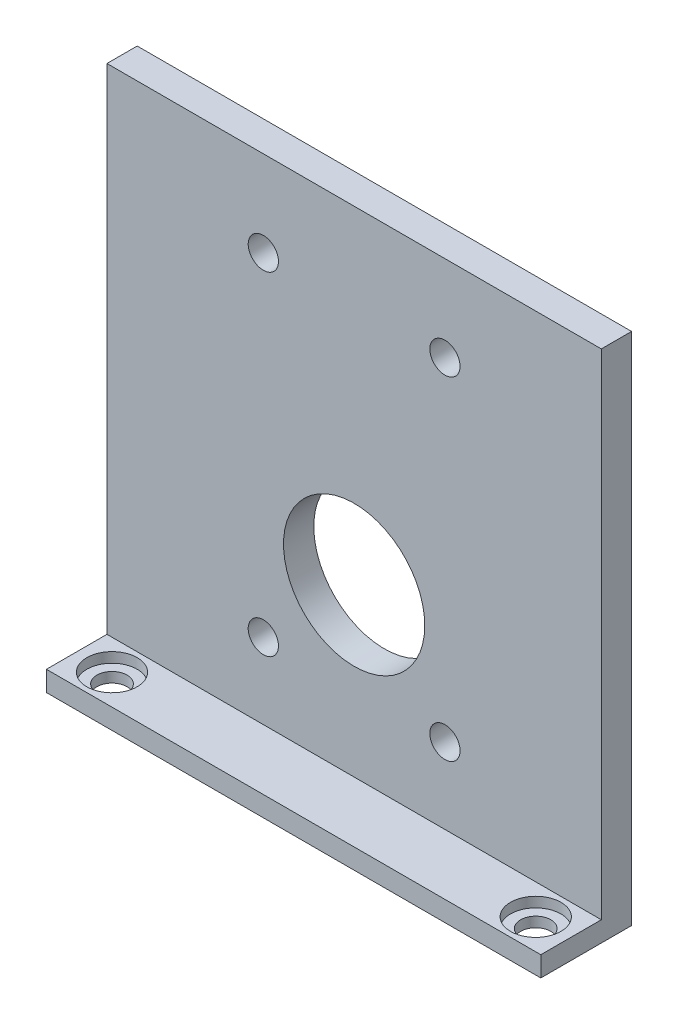
SolidWorks part; units mm, degrees
ref_plane "Front Plane" through (0, 0, 0) normal (0, 0, 1) x (1, 0, 0)
ref_plane "Top Plane" through (0, 0, 0) normal (0, 1, 0) x (1, 0, 0)
ref_plane "Right Plane" through (0, 0, 0) normal (1, 0, 0) x (0, 0, -1)
sketch "Sketch1" plane through (0, 0, 0) normal (0, 1, 0) x (1, 0, 0)
  line L1 (-24.5, 4.5) -> (24.5, 4.5)
  line L2 (-24.5, 4.5) -> (-24.5, -4.5)
  line L3 (-24.5, -4.5) -> (24.5, -4.5)
  line L4 (24.5, 4.5) -> (24.5, -4.5)
  line L5 (-24.5, 4.5) -> (24.5, -4.5) construction
  line L6 (-24.5, -4.5) -> (24.5, 4.5) construction
  point P0 (0, 0)
  dimension "D1" = 9
  dimension "D2" = 49
extrude "Boss-Extrude1" add sketch "Sketch1" along normal blind 2
sketch "Sketch2" plane through (0, 2, 0) normal (0, 1, 0) x (1, 0, 0)
  line L0 (-24.5, 1.5) -> (24.5, 1.5) construction
  line L1 (-24.5, 4.5) -> (-24.5, -4.5) construction
  line L2 (24.5, -4.5) -> (24.5, 4.5) construction
  line L3 (24.5, 4.5) -> (-24.5, 4.5) construction
  line L5 (-24.5, 4.5) -> (24.5, 4.5)
  line L6 (-24.5, 4.5) -> (-24.5, 1.5)
  line L7 (-24.5, 1.5) -> (24.5, 1.5)
  line L8 (24.5, 4.5) -> (24.5, 1.5)
  dimension "D1" = 3
extrude "Boss-Extrude2" add sketch "Sketch2" along normal blind 49
sketch "Sketch3" plane through (0, 0, -1.5) normal (0, 0, 1) x (1, 0, 0)
  line L0 (0, 2) -> (0, 51) construction
  line L1 (-24.5, 2) -> (24.5, 2) construction
  line L2 (-24.5, 51) -> (24.5, 51) construction
  line L3 (-24.5, 49.5) -> (24.5, 49.5) construction
  line L4 (-24.5, 51) -> (-24.5, 2) construction
  line L5 (24.5, 51) -> (24.5, 2) construction
  line L6 (-24.5, 3.5) -> (24.5, 3.5) construction
  line L7 (-24.5, 2) -> (24.5, 2) construction
  line L8 (-23, 51) -> (-23, 2) construction
  line L9 (23, 51) -> (23, 2) construction
  circle A0 centre (-9, 9.5) radius 1.5
  circle A1 centre (9, 9.5) radius 1.5
  circle A2 centre (-9, 42.5) radius 1.5
  circle A3 centre (9, 42.5) radius 1.5
  circle A4 centre (0, 18.5) radius 7
  dimension "D5" = 3
  dimension "D8" = 9
  dimension "D10" = 9
  dimension "D14" = 9
  dimension "D15" = 14
  dimension "D1" = 1.5
  dimension "D2" = 1.5
  dimension "D3" = 1.5
  dimension "D4" = 1.5
  dimension "D6" = 6
  dimension "D7" = 9
  dimension "D9" = 6
  dimension "D11" = 9
  dimension "D12" = 33
  dimension "D13" = 33
extrude "Cut-Extrude1" cut sketch "Sketch3" against normal blind 3
sketch "Sketch4" plane through (0, 2, 0) normal (0, 1, 0) x (1, 0, 0)
  line L0 (-24.5, -1.5) -> (24.5, -1.5) construction
  line L1 (-24.5, 1.5) -> (-24.5, -4.5) construction
  line L2 (24.5, -4.5) -> (24.5, 1.5) construction
  circle A0 centre (-21, -1.5) radius 2.5
  circle A1 centre (21, -1.5) radius 2.5
  dimension "D1" = 3.5
  dimension "D2" = 3.5
extrude "Cut-Extrude2" cut sketch "Sketch4" against normal blind 1
sketch "Sketch5" plane through (0, 1, 0) normal (0, 1, 0) x (1, 0, 0)
  circle A0 centre (-21, -1.5) radius 1.5
extrude "Cut-Extrude3" cut sketch "Sketch5" against normal blind 2
sketch "Sketch6" plane through (0, 1, 0) normal (0, 1, 0) x (1, 0, 0)
  circle A0 centre (21, -1.5) radius 1.5
extrude "Cut-Extrude4" cut sketch "Sketch6" against normal blind 2
